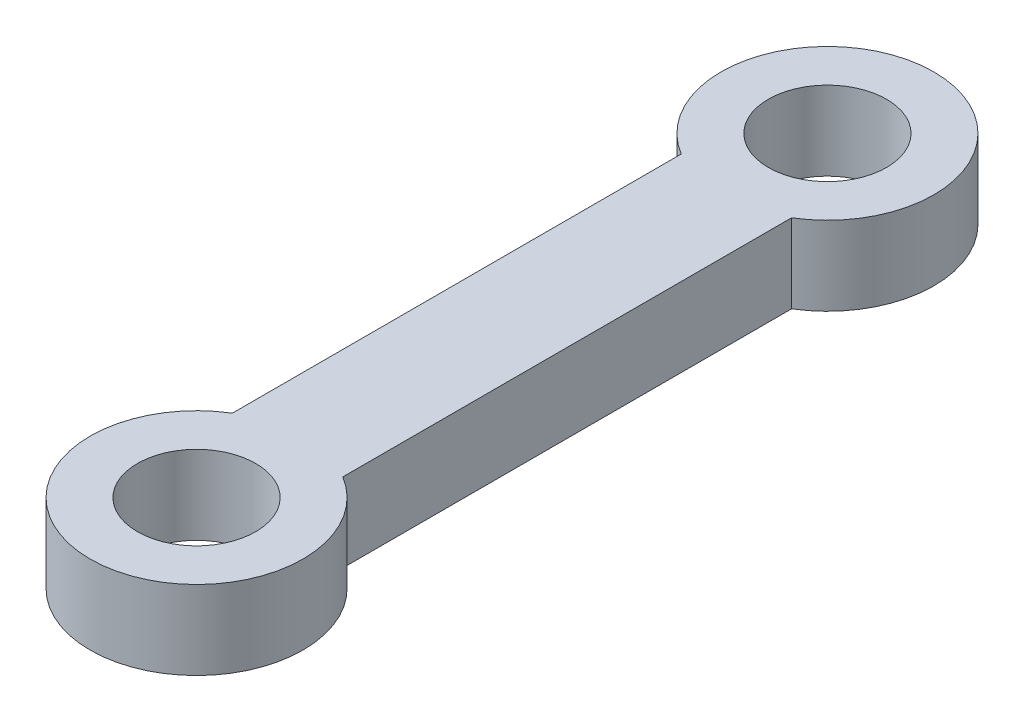
SolidWorks part; units mm, degrees
ref_plane "前视基准面" through (0, 0, 0) normal (0, 0, 1) x (1, 0, 0)
ref_plane "上视基准面" through (0, 0, 0) normal (0, 1, 0) x (1, 0, 0)
ref_plane "右视基准面" through (0, 0, 0) normal (1, 0, 0) x (0, 0, -1)
sketch "草图1" plane through (0, 0, 0) normal (0, 1, 0) x (1, 0, 0)
  line L0 (0, 0) -> (0, -16) construction
  line L1 (-1.4, -2.3087) -> (-1.4, -13.6913)
  line L2 (1.4, -2.3087) -> (1.4, -13.6913)
  arc A0 (1.4, -2.3087) -> (-1.4, -2.3087) centre (0, 0) ccw
  circle A1 centre (0, 0) radius 1.5
  circle A2 centre (0, -16) radius 1.5
  arc A3 (-1.4, -13.6913) -> (1.4, -13.6913) centre (0, -16) ccw
  dimension "D1" = 3
  dimension "D2" = 5.4
  dimension "D3" = 16
  dimension "D4" = 2.8
extrude "凸台-拉伸1" add sketch "草图1" along normal blind 2
